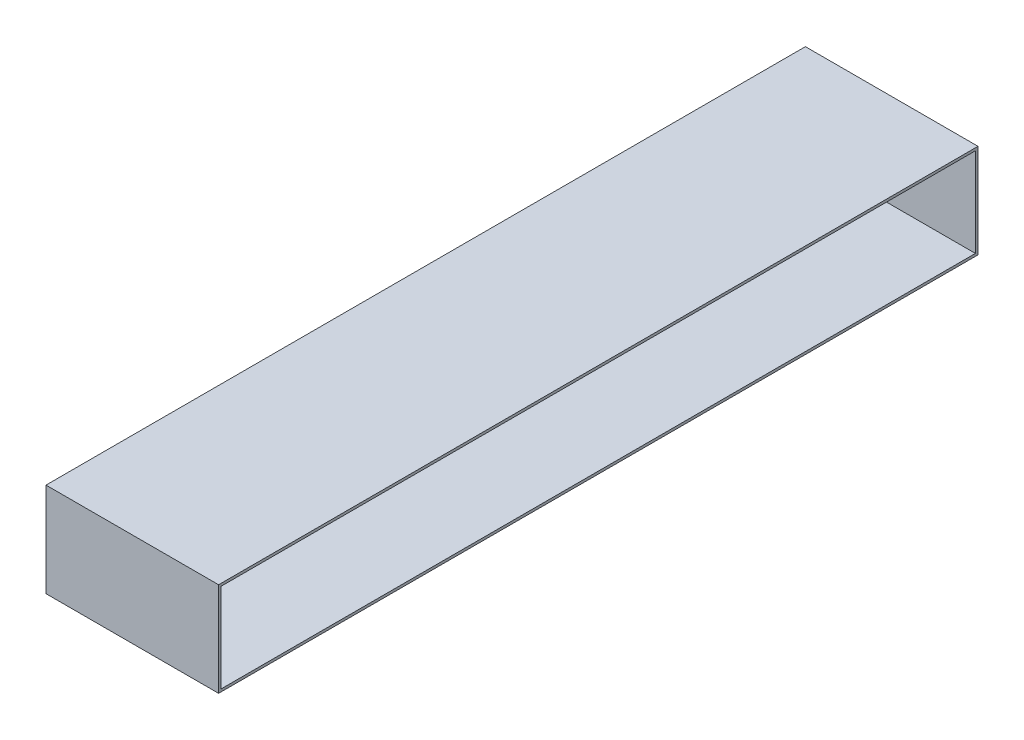
SolidWorks part; units mm, degrees
ref_plane "Front Plane" through (0, 0, 0) normal (0, 0, 1) x (1, 0, 0)
ref_plane "Top Plane" through (0, 0, 0) normal (0, 1, 0) x (1, 0, 0)
ref_plane "Right Plane" through (0, 0, 0) normal (1, 0, 0) x (0, 0, -1)
sketch "Sketch3" plane through (0, 0, 0) normal (1, 0, 0) x (0, 0, -1)
  line L2 (52.2948, 114.6106) -> (932.2948, 114.6106)
  line L3 (932.2948, 5.6106) -> (932.2948, 114.6106)
  line L4 (55.2948, 8.6106) -> (929.2948, 8.6106)
  line L5 (55.2948, 8.6106) -> (55.2948, 111.6106)
  line L6 (55.2948, 111.6106) -> (929.2948, 111.6106)
  line L7 (929.2948, 8.6106) -> (929.2948, 111.6106)
  line L8 (52.2948, 5.6106) -> (932.2948, 5.6106)
  line L9 (52.2948, 5.6106) -> (52.2948, 114.6106)
  dimension "D1" = 874
  dimension "D2" = 103
  dimension "D3" = 3
extrude "Boss-Extrude2" add sketch "Sketch3" along normal blind 200 contours L9 L8 L3 L2 L7 L4 L5 L6
